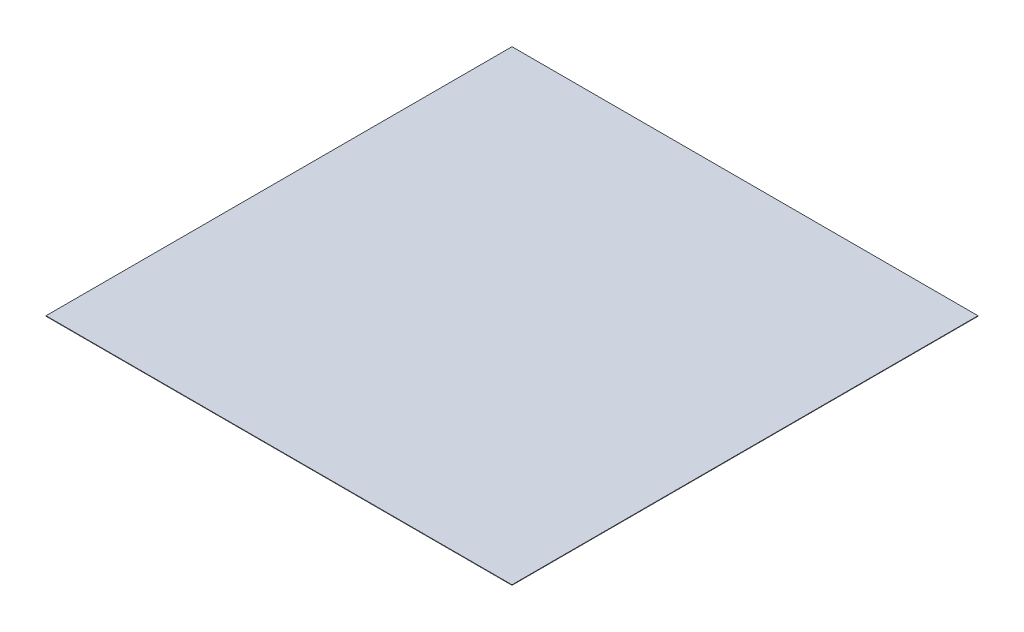
SolidWorks part; units mm, degrees
ref_plane "Спереди" through (0, 0, 0) normal (0, 0, 1) x (1, 0, 0)
ref_plane "Сверху" through (0, 0, 0) normal (0, 1, 0) x (1, 0, 0)
ref_plane "Справа" through (0, 0, 0) normal (1, 0, 0) x (0, 0, -1)
sketch "Эскиз1" plane through (0, 0, 0) normal (0, 0, 1) x (1, 0, 0)
  line L1 (0, 0) -> (1000, 0)
  line L2 (0, 0) -> (0, 1)
  line L3 (0, 1) -> (1000, 1)
  line L4 (1000, 0) -> (1000, 1)
  dimension "D1" = 1
  dimension "D2" = 1000
extrude "Бобышка-Вытянуть1" add sketch "Эскиз1" along normal blind 1000 contours L1 L4 L3 L2
